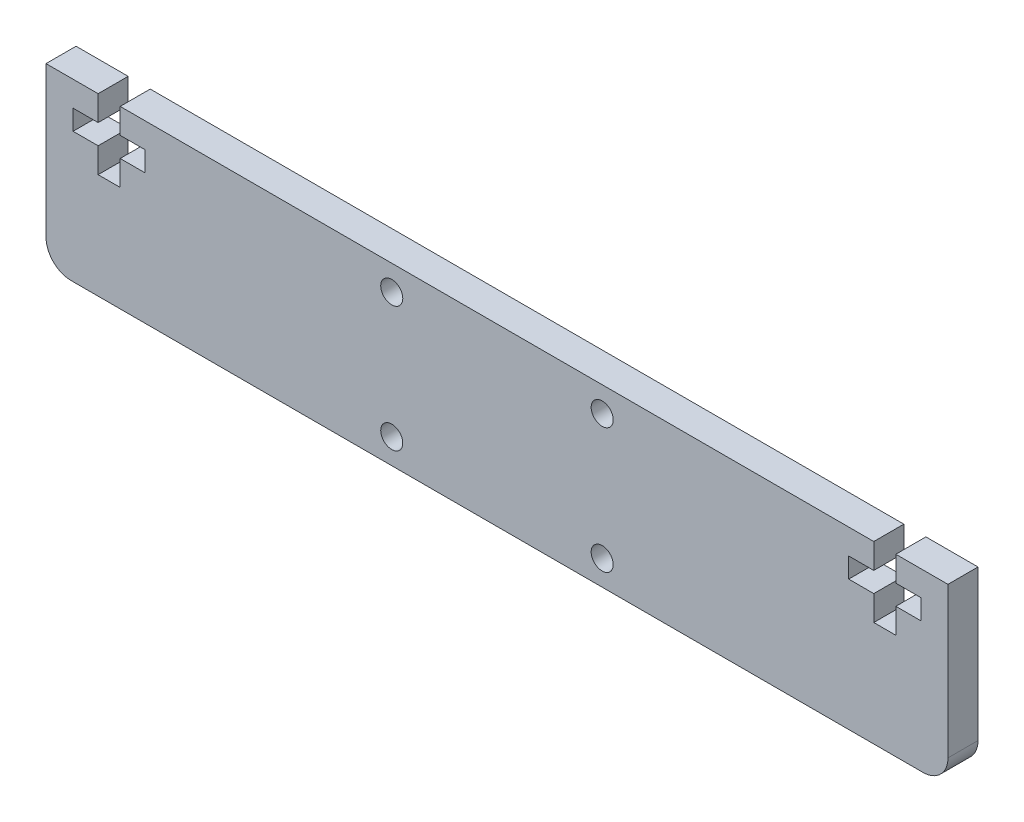
SolidWorks part; units mm, degrees
ref_plane "Front Plane" through (0, 0, 0) normal (0, 0, 1) x (1, 0, 0)
ref_plane "Top Plane" through (0, 0, 0) normal (0, 1, 0) x (1, 0, 0)
ref_plane "Right Plane" through (0, 0, 0) normal (1, 0, 0) x (0, 0, -1)
sketch "Sketch1" plane through (0, 0, 0) normal (0, 0, 1) x (1, 0, 0)
  line L0 (-45, 0) -> (45, 0) construction
  line L1 (-45, -8.75) -> (45, -8.75)
  line L2 (-45, -8.75) -> (-45, 8.75)
  line L3 (-45, 8.75) -> (45, 8.75) construction
  line L4 (45, -8.75) -> (45, 8.75)
  line L5 (-45, -8.75) -> (45, 8.75) construction
  line L6 (-45, 8.75) -> (45, -8.75) construction
  line L19 (0, 8.75) -> (0, -8.75) construction
  line L47 (-37.6, 8.75) -> (-37.6, 6.25)
  line L48 (-37.6, 6.25) -> (-35.1, 6.25)
  line L49 (-35.1, 6.25) -> (-35.1, 4.25)
  line L50 (-35.1, 4.25) -> (-37.6, 4.25)
  line L51 (-37.6, 4.25) -> (-37.6, 1.75)
  line L52 (-37.6, 1.75) -> (-39.8, 1.75)
  line L70 (-39.8, 1.75) -> (-39.8, 4.25)
  line L71 (-39.8, 4.25) -> (-42.3, 4.25)
  line L72 (-42.3, 4.25) -> (-42.3, 6.25)
  line L73 (-42.3, 6.25) -> (-39.8, 6.25)
  line L74 (-39.8, 6.25) -> (-39.8, 8.75)
  line L75 (39.8, 6.25) -> (39.8, 8.75)
  line L76 (42.3, 6.25) -> (39.8, 6.25)
  line L77 (42.3, 4.25) -> (42.3, 6.25)
  line L78 (39.8, 4.25) -> (42.3, 4.25)
  line L79 (39.8, 1.75) -> (39.8, 4.25)
  line L80 (37.6, 1.75) -> (39.8, 1.75)
  line L81 (37.6, 4.25) -> (37.6, 1.75)
  line L82 (35.1, 4.25) -> (37.6, 4.25)
  line L83 (35.1, 6.25) -> (35.1, 4.25)
  line L84 (37.6, 6.25) -> (35.1, 6.25)
  line L85 (37.6, 8.75) -> (37.6, 6.25)
  line L86 (-45, 8.75) -> (-39.8, 8.75)
  line L87 (-37.6, 8.75) -> (37.6, 8.75)
  line L88 (39.8, 8.75) -> (45, 8.75)
  circle A5 centre (-10.5, 6.25) radius 1.1
  circle A9 centre (-10.5, -6.25) radius 1.1
  circle A12 centre (10.5, -6.25) radius 1.1
  circle A13 centre (10.5, 6.25) radius 1.1
  point P0 (0, 0)
  dimension "D3" = 2.2
  dimension "D1" = 90
  dimension "D2" = 17.5
  dimension "D5" = 10.5
  dimension "D6" = 6.25
  dimension "D13" = 2.2
  dimension "D14" = 2.5
  dimension "D15" = 2
  dimension "D16" = 2.5
  dimension "D17" = 35.1
  dimension "D18" = 1.75
extrude "Boss-Extrude1" add sketch "Sketch1" along normal blind 3
fillet "Fillet1" radius 2.5 2 edges at (-45, -8.75, 1.5) (45, -8.75, 1.5)
